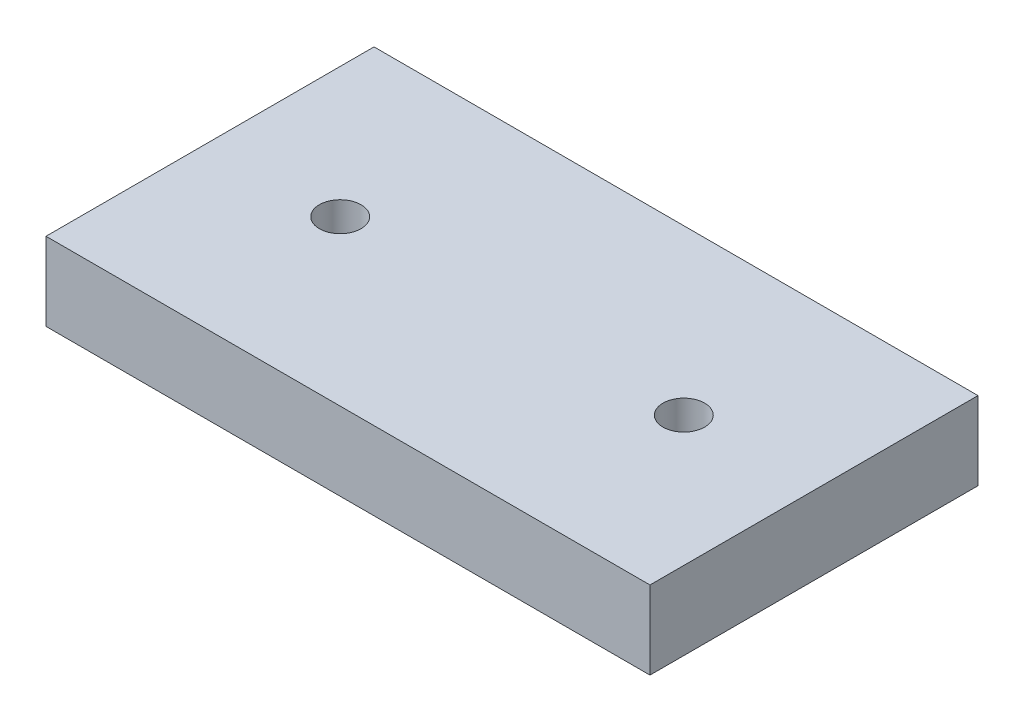
SolidWorks part; units mm, degrees
ref_plane "Alzado" through (0, 0, 0) normal (0, 0, 1) x (1, 0, 0)
ref_plane "Planta" through (0, 0, 0) normal (0, 1, 0) x (1, 0, 0)
ref_plane "Vista lateral" through (0, 0, 0) normal (1, 0, 0) x (0, 0, -1)
sketch "Croquis1" plane through (0, 0, 0) normal (0, 1, 0) x (1, 0, 0)
  line L0 (0, 31.5) -> (116, 31.5) construction
  line L1 (0, 0) -> (116, 0)
  line L2 (0, 0) -> (0, 63)
  line L3 (0, 63) -> (116, 63)
  line L4 (116, 0) -> (116, 63)
  line L5 (58, 63) -> (58, 0) construction
  circle A0 centre (25, 31.5) radius 4
  circle A1 centre (91, 31.5) radius 4
  dimension "D3" = 8
  dimension "D4" = 8
  dimension "D1" = 116
  dimension "D2" = 63
  dimension "D5" = 33
  dimension "D7" = 33
extrude "Saliente-Extruir1" add sketch "Croquis1" along normal blind 15
